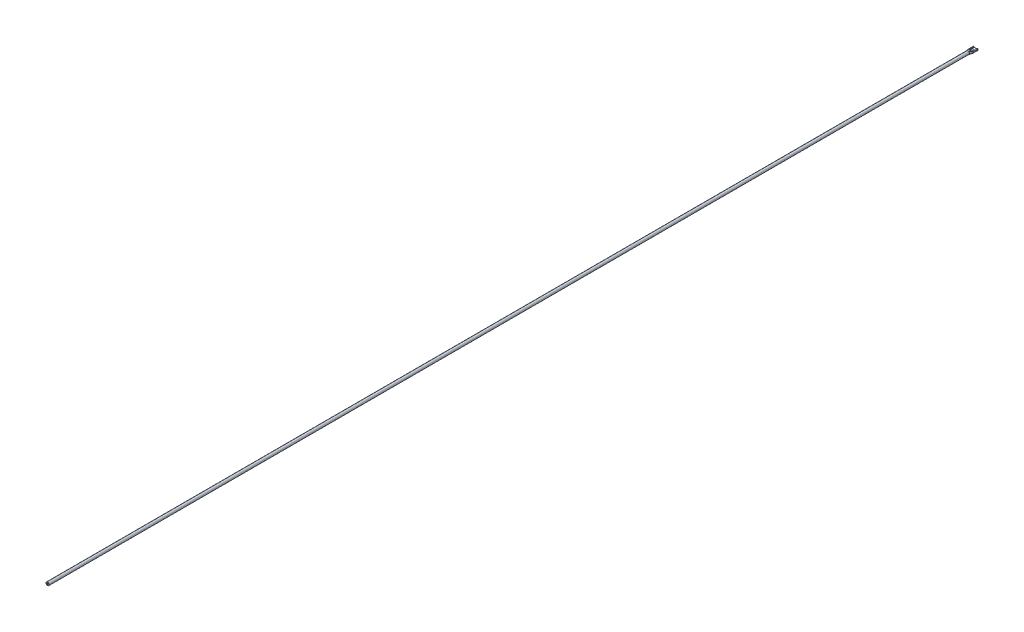
SolidWorks part; units mm, degrees
material "A286 Iron Base Superalloy"
ref_plane "Plan de face" through (0, 0, 0) normal (0, 0, 1) x (1, 0, 0)
ref_plane "Plan de dessus" through (0, 0, 0) normal (0, 1, 0) x (1, 0, 0)
ref_plane "Plan de droite" through (0, 0, 0) normal (1, 0, 0) x (0, 0, -1)
sketch "Esquisse1" plane through (0, 0, 0) normal (0, 0, 1) x (1, 0, 0)
  circle A0 centre (0, 0) radius 15
  dimension "D1" = 30
extrude "Boss.-Extru.1" add sketch "Esquisse1" along normal blind 450
sketch "Sketch4" plane through (0, 0, 0) normal (0, 0, -1) x (-1, 0, 0)
  line L1 (-14.6969, 3) -> (14.6969, 3)
  line L2 (-14.6969, 3) -> (-14.6969, 15)
  line L3 (-14.6969, 15) -> (14.6969, 15)
  line L4 (14.6969, 3) -> (14.6969, 15)
  circle A0 centre (0, 0) radius 15 construction
  dimension "D1" = 3
extrude "Cut-Extrude1" cut sketch "Sketch4" against normal blind 32
sketch "Sketch5" plane through (0, 3, 0) normal (0, 1, 0) x (1, 0, 0)
  line L0 (0, 0) -> (0, -32)
  line L1 (14.6969, 0) -> (-14.6969, 0) construction
  line L2 (0, -32) -> (-10, -32)
  line L3 (-10, -32) -> (-10, -27.9438)
  line L4 (-10, -27.9438) -> (-3, -23.9023)
  line L5 (-3, -23.9023) -> (-3, -21.9023)
  line L6 (-3, -21.9023) -> (-12.5, -18.4446)
  line L7 (-12.5, -18.4446) -> (-12.5, -15.9446)
  line L8 (-12.5, -15.9446) -> (-6.5, -12.4805)
  line L9 (-6.5, -12.4805) -> (-6.5, -10.4805)
  line L10 (-6.5, -10.4805) -> (-15, -7.3868)
  line L11 (-15, -7.3868) -> (-15, -4.8868)
  line L12 (-15, -4.8868) -> (-10, -2)
  line L13 (-10, -2) -> (-10, 0)
  line L14 (-10, 0) -> (0, 0)
  point P4 (-6.5, -11.4805)
  dimension "D1" = 10
  dimension "D2" = 2
  dimension "D3" = 120
  dimension "D4" = 15
  dimension "D5" = 2.5
  dimension "D6" = 110
  dimension "D7" = 2
  dimension "D8" = 6.5
  dimension "D9" = 2.5
  dimension "D10" = 110
  dimension "D11" = 12.5
  dimension "D12" = 3
  dimension "D13" = 120
  dimension "D14" = 10
  dimension "D15" = 2
  dimension "D16" = 32
extrude "Cut-Extrude2" cut sketch "Sketch5" against normal blind 3.75
sketch "Sketch6" plane through (0, 3, 0) normal (0, 1, 0) x (1, 0, 0)
  line L0 (-10, 0) -> (-14.6969, 0) construction
  line L1 (-10, 0) -> (-10.5, 0)
  line L2 (-10, 0) -> (-10, -2.2887)
  line L3 (-10, -2.2887) -> (-10.5, -2.2887)
  line L4 (-10.5, 0) -> (-10.5, -2.2887)
  line L5 (-10, -2) -> (-14.6969, -4.7118) construction
  line L12 (-6.75, -12.6248) -> (-6.75, -10.9216)
  line L13 (-6.5, -12.4805) -> (-12.5, -15.9446) construction
  line L14 (-6.75, -10.9216) -> (-15, -7.9188)
  line L15 (-15, -7.9188) -> (-15, -7.3868)
  line L16 (-15, -7.3868) -> (-6.5, -10.4805)
  line L17 (-6.5, -10.4805) -> (-6.5, -12.4805) construction
  line L18 (-6.5, -10.4805) -> (-6.5, -12.4805)
  line L19 (-6.5, -12.4805) -> (-6.75, -12.6248)
  line L20 (-6.5, -10.4805) -> (-14.6969, -7.4971) construction
  line L21 (0, 0) -> (-10, 0) construction
  line L22 (-12.5, -15.9446) -> (-13, -16.2333)
  line L23 (-12.5, -15.9446) -> (-12.5, -18.4446) construction
  line L24 (-13, -16.2333) -> (-13, -18.7947)
  line L25 (-13, -18.7947) -> (-3.25, -22.3434)
  line L26 (-3.25, -22.3434) -> (-3.25, -24.0467)
  line L27 (-3, -23.9023) -> (-10, -27.9438) construction
  line L28 (-3.25, -24.0467) -> (-3, -23.9023)
  line L29 (-3, -23.9023) -> (-3, -21.9023)
  line L30 (-3, -21.9023) -> (-3, -23.9023) construction
  line L31 (-3, -21.9023) -> (-12.5, -18.4446)
  line L32 (-12.5, -18.4446) -> (-3, -21.9023) construction
  line L33 (-12.5, -18.4446) -> (-12.5, -15.9446)
  line L34 (-10, -32) -> (-10, -27.9438)
  line L35 (-10, -27.9438) -> (-10, -32) construction
  line L36 (-10, -27.9438) -> (-10.5, -28.2324)
  line L37 (-10.5, -28.2324) -> (-10.5, -32)
  line L38 (-10.5, -32) -> (-10, -32)
  line L39 (-10, -32) -> (-14.6969, -32) construction
  point P46 (-10, -29.9719)
  dimension "D1" = 0.5
  dimension "D2" = 0.25
  dimension "D3" = 15
  dimension "D4" = 0.5
  dimension "D5" = 0.5
  dimension "D6" = 0.25
  dimension "D7" = 0.5
  dimension "D8" = 0.5
extrude "Cut-Extrude3" cut sketch "Sketch6" against normal up to surface (3.75 mm away) up to face at (-8.1402, -0.75, 14.9549)
mirror "Mirror2" about plane through (0, 0, 0) normal (1, 0, 0) of "Cut-Extrude2", "Cut-Extrude3"
fillet "Fillet1" radius 0.5 10 edges at (-10.5, 1.125, 2.2887) (-6.75, 1.125, 10.9216) (-6.75, 1.125, 12.6248) (-3.25, 1.125, 22.3434) (-3.25, 1.125, 24.0467) (3.25, 1.125, 24.0467) (3.25, 1.125, 22.3434) (6.75, 1.125, 12.6248) (6.75, 1.125, 10.9216) (10.5, 1.125, 2.2887)
fillet "Fillet2" radius 1.5 8 edges at (-13, 1.125, 18.7947) (-10.5, 1.125, 32) (-10.5, 1.125, 28.2324) (-13, 1.125, 16.2333) (10.5, 1.125, 32) (10.5, 1.125, 28.2324) (13, 1.125, 18.7947) (13, 1.125, 16.2333)
sketch "Sketch7" plane through (0, 0, 0) normal (0, 1, 0) x (1, 0, 0)
  line L0 (10, -450) -> (10, -50.6603)
  line L1 (-15, -450) -> (15, -450) construction
  line L2 (10, -50.6603) -> (15, -32)
  line L3 (15, -450) -> (15, -7.9188) construction
  line L4 (15, -32) -> (15, -450)
  line L5 (15, -450) -> (10, -450)
  line L6 (0, -450) -> (0, -32) construction
  dimension "D1" = 10
  dimension "D2" = 32
  dimension "D3" = 15
revolve "Cut-Revolve1" cut sketch "Sketch7" angle 360 about axis through (0, 0, 450) along (0, 0, -1)
sketch "Sketch8" plane through (0, 0, 0) normal (1, 0, 0) x (0, 0, -1)
  line L1 (-52.6603, 10) -> (-32, 15)
  line L3 (-52.6603, 10) -> (-32, 10) construction
  line L4 (-32, 3) -> (-32, 15) construction
  line L5 (-32, 10) -> (-32, 15)
  line L6 (-32, 3) -> (-34, 3)
  line L7 (-32, 3) -> (-32, 10)
  line L8 (-34, 3) -> (-52.6603, 10)
  line L9 (-50.6603, 10) -> (-450, 10) construction
  line L10 (-50.6603, 10) -> (-50.6603, -10) construction
  dimension "D1" = 2
  dimension "D2" = 2
extrude "Cut-Extrude4" cut sketch "Sketch8" against normal mid plane 30
sketch "Sketch9" plane through (0, 0, 0) normal (1, 0, 0) x (0, 0, -1)
  line L0 (0, -15) -> (0, 3) construction
  line L4 (0, -8) -> (0, -15)
  line L5 (0, -8) -> (-34, -8)
  line L8 (-32, 0) -> (0, 0) construction
  line L9 (-32, -15) -> (-32, 3) construction
  line L10 (-34, -8) -> (-52.6603, -10)
  line L11 (-450, -10) -> (-50.6603, -10) construction
  line L13 (-52.6603, -15) -> (0, -15)
  line L14 (-52.6603, -10) -> (-52.6603, -15)
  line L15 (-52.6603, -10) -> (-52.6603, 10) construction
  dimension "D1" = 8
  dimension "D2" = 2
extrude "Cut-Extrude5" cut sketch "Sketch9" against normal mid plane 30
sketch "Sketch11" plane through (0, 3, 0) normal (0, 1, 0) x (1, 0, 0)
  line L0 (10.75, -2.433) -> (14.9812, -4.8759) construction
  line L1 (14.3, -4.4826) -> (15, -4.4826)
  line L2 (14.3, -4.4826) -> (14.3, -4.8868)
  line L3 (14.3, -4.8868) -> (15, -4.8868)
  line L4 (15, -4.4826) -> (15, -4.8868)
  line L5 (-10.75, -2.433) -> (-14.6969, -4.7118) construction
  line L6 (-14.3, -4.4826) -> (-15, -4.4826)
  line L7 (-14.3, -4.4826) -> (-14.3, -4.8868)
  line L8 (-14.3, -4.8868) -> (-15, -4.8868)
  line L9 (-15, -4.4826) -> (-15, -4.8868)
  line L20 (14.9812, -7.9257) -> (7.079, -10.8019) construction
  line L21 (14.3, -8.1736) -> (15, -8.1736)
  line L22 (14.3, -8.1736) -> (14.3, -6.4008)
  line L23 (14.3, -6.4008) -> (15, -6.4008)
  line L24 (15, -8.1736) -> (15, -6.4008)
  line L26 (-14.9812, -7.9257) -> (-7.079, -10.8019) construction
  line L27 (-14.3, -8.1736) -> (-15, -8.1736)
  line L28 (-14.3, -8.1736) -> (-14.3, -6.4008)
  line L29 (-14.3, -6.4008) -> (-15, -6.4008)
  line L30 (-15, -8.1736) -> (-15, -6.4008)
  line L32 (14.9812, -4.8759) -> (14.9812, -7.9257) construction
  line L34 (-14.9812, -7.9257) -> (-14.9812, -4.8759) construction
  point P32 (14.9812, -6.4008)
  point P36 (-14.9812, -6.4008)
  dimension "D1" = 0.7
  dimension "D2" = 0.7
extrude "Cut-Extrude7" cut sketch "Sketch11" against normal up to surface (3.75 mm away) up to face at (0, -0.75, 16.5113)
sketch "Sketch12" plane through (0, 0, 450) normal (0, 0, 1) x (1, 0, 0)
  circle A0 centre (0, 0) radius 10
  dimension "D1" = 20
extrude "Boss-Extrude1" add sketch "Sketch12" along normal blind 5550
hole_wizard "M10 Tapped Hole1" positions "Sketch13" profile "Sketch14" tap size "M10" standard "ISO"
sketch "Sketch13" plane through (0, 0, 6000) normal (0, 0, 1) x (1, 0, 0)
  point P0 (0, 0)
sketch "Sketch14" plane through (0, 0, 6000) normal (1, 0, 0) x (0, -1, 0)
  line L0 (0, 0) -> (0, 30.0537)
  line L1 (0, 30.0537) -> (4.25, 27.5)
  line L2 (4.25, 27.5) -> (4.25, 0)
  line L5 (4.25, 0) -> (0, 0)
  line L10 (0, 30.0537) -> (-4.25, 27.5) construction
  line L11 (0, -6.35) -> (0, 107.95) construction
  dimension "Tap Drill Dia." = 8.5
  dimension "Tap Drill Depth" = 27.5
  dimension "Drill Angle" = 118
cosmetic thread "Hole Thread1" parameters "D1"=20, "D2"=10
hole_wizard "M4 Tapped Hole1" positions "Sketch15" profile "Sketch16" tap size "M4" standard "ISO"
sketch "Sketch15" plane through (0, -0.75, 0) normal (0, 1, 0) x (1, 0, 0)
  line L0 (0, -32) -> (0, -8.1736) construction
  point P0 (0, -16.5)
  dimension "D1" = 16.5
sketch "Sketch16" plane through (0, -0.75, 16.5) normal (1, 0, 0) x (0, 0, 1)
  line L0 (0, 0) -> (0, 12.4914)
  line L1 (0, 12.4914) -> (1.65, 11.5)
  line L2 (1.65, 11.5) -> (1.65, 0)
  line L5 (1.65, 0) -> (0, 0)
  line L10 (0, 12.4914) -> (-1.65, 11.5) construction
  line L11 (0, -6.35) -> (0, 107.95) construction
  dimension "Tap Drill Dia." = 3.3
  dimension "Tap Drill Depth" = 11.5
  dimension "Drill Angle" = 118
cosmetic thread "Hole Thread2" parameters "D1"=7.25, "D2"=4
